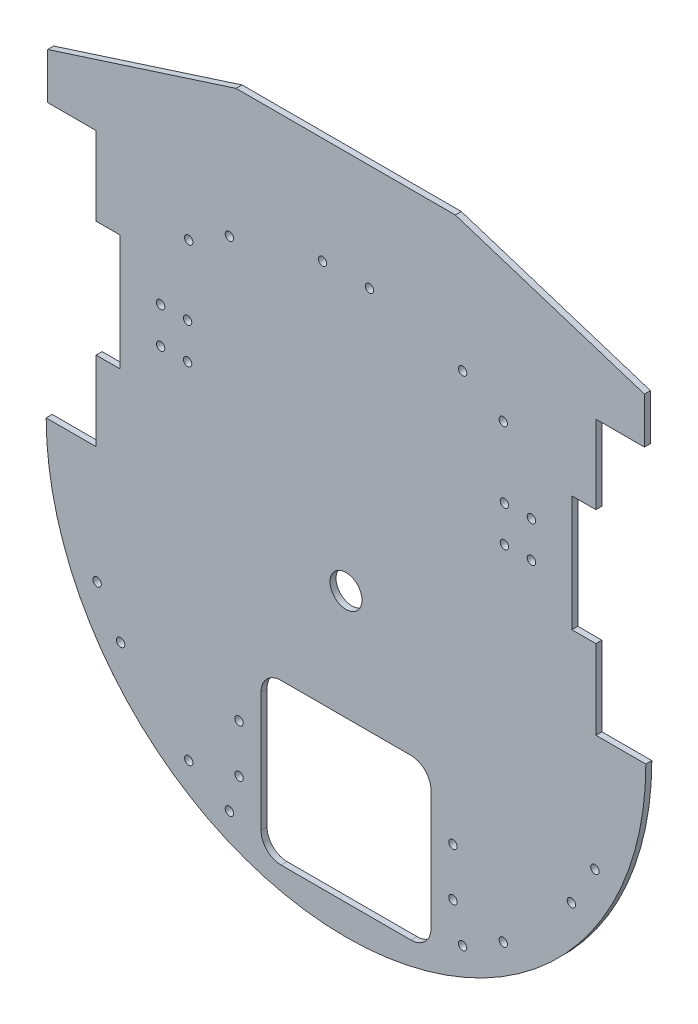
SolidWorks part; units mm, degrees
ref_plane "前视基准面" through (0, 0, 0) normal (0, 0, 1) x (1, 0, 0)
ref_plane "上视基准面" through (0, 0, 0) normal (0, 1, 0) x (1, 0, 0)
ref_plane "右视基准面" through (0, 0, 0) normal (1, 0, 0) x (0, 0, -1)
sketch "草图1" plane through (0, 0, 0) normal (0, 0, 1) x (1, 0, 0)
  line L0 (-172.2675, 0) -> (180.3743, 0) construction
  line L1 (-150, 0) -> (-125.0004, 0)
  line L2 (150, 0) -> (125.0004, 0)
  line L3 (-125.0004, 0) -> (-125.0004, 39.6998)
  line L4 (125.0004, 0) -> (125.0004, 39.6998)
  line L5 (-149.2919, 159.9629) -> (-55, 190.2481)
  line L6 (42.5, -95) -> (42.5, -65)
  line L7 (160.7954, 68.7) -> (-155.1254, 68.7) construction
  line L8 (-42.5, -95) -> (-42.5, -65)
  line L9 (54.6877, 190.2481) -> (149.2919, 159.9629)
  line L10 (42.5, -95) -> (-42.5, -95) construction
  line L11 (-86.0004, 86.026) -> (-86.0004, 54.054) construction
  line L12 (42.5, -95) -> (42.5, -125)
  line L13 (-32.5, -135) -> (32.5, -135)
  line L14 (0, -145) -> (104.3732, -145) construction
  line L15 (-42.5, -125) -> (-42.5, -95)
  line L17 (125.0004, 97.6998) -> (113.0004, 97.6998)
  line L18 (-125.0004, 97.6998) -> (-125.0004, 136.9629)
  line L20 (125.0004, 39.6998) -> (113.0004, 39.6998)
  line L22 (-125.0004, 39.6998) -> (-113.0004, 39.6998)
  line L23 (-125.0004, 97.6998) -> (-113.0004, 97.6998)
  line L24 (125.0004, 136.9629) -> (125.0004, 97.6998)
  line L25 (32.5, -55) -> (-32.5, -55)
  line L27 (0, 25.0818) -> (0, -21.9182) construction
  line L31 (149.2919, -14.5582) -> (149.2919, 172.9128) construction
  line L36 (0, -55) -> (0, -174.5161) construction
  line L46 (-149.2919, 136.9629) -> (-149.2919, 159.9629)
  line L48 (-125.0004, 136.9629) -> (-149.2919, 136.9629)
  line L87 (-149.2919, -14.5582) -> (-149.2919, 172.9128) construction
  line L92 (54.6877, 190.2481) -> (-55, 190.2481)
  line L104 (149.2919, 136.9629) -> (149.2919, 159.9629)
  line L122 (125.0004, 136.9629) -> (149.2919, 136.9629)
  line L125 (-113.0004, 97.6998) -> (-113.0004, 39.6998)
  line L126 (113.0004, 97.6998) -> (113.0004, 39.6998)
  circle A0 centre (-92.7504, 77.7) radius 2.1
  circle A1 centre (-92.7504, 59.7) radius 2.1
  circle A2 centre (-53.5, -83) radius 2.1
  circle A3 centre (-53.5, -107) radius 2.1
  circle A4 centre (53.5, -107) radius 2.1
  circle A5 centre (53.5, -83) radius 2.1
  circle A6 centre (-79.2504, 59.7) radius 2.1
  circle A7 centre (-79.2504, 77.7) radius 2.1
  circle A8 centre (79.2504, 59.7) radius 2.1
  circle A9 centre (92.7504, 59.7) radius 2.1
  arc A10 (-32.5, -135) -> (-42.5, -125) centre (-32.5, -125) cw
  circle A11 centre (79.2504, 77.7) radius 2.1
  circle A12 centre (92.7504, 77.7) radius 2.1
  circle A13 centre (0, 0) radius 8
  circle A15 centre (-58.3242, -124.5205) radius 2.1
  circle A16 centre (-78.6758, -112.7705) radius 2.1
  circle A17 centre (-112.7705, -78.6758) radius 2.1
  circle A18 centre (-124.5205, -58.3242) radius 2.1
  circle A23 centre (-78.6758, 112.7705) radius 2.1
  circle A24 centre (-58.3242, 124.5205) radius 2.1
  circle A25 centre (-11.75, 137) radius 2.1
  circle A26 centre (11.75, 137) radius 2.1
  circle A27 centre (58.3242, 124.5205) radius 2.1
  circle A28 centre (78.6758, 112.7705) radius 2.1
  arc A31 (32.5, -135) -> (42.5, -125) centre (32.5, -125) ccw
  arc A32 (42.5, -65) -> (32.5, -55) centre (32.5, -65) ccw
  circle A35 centre (124.5205, -58.3242) radius 2.1
  circle A36 centre (112.7705, -78.6758) radius 2.1
  circle A37 centre (78.6758, -112.7705) radius 2.1
  circle A38 centre (58.3242, -124.5205) radius 2.1
  arc A41 (-150, 0) -> (150, 0) centre (0, 0) ccw
  arc A43 (-42.5, -65) -> (-32.5, -55) centre (-32.5, -65) cw
  point P105 (0, 0)
  dimension "D5" = 40
  dimension "D6" = 136.9629
  dimension "D7" = 12
  dimension "D8" = 68.7
  dimension "D9" = 11
  dimension "D10" = 6.75
  dimension "D11" = 9
  dimension "D12" = 145
  dimension "D16" = 4.2
  dimension "D18" = 55
  dimension "D19" = 29.0002
  dimension "D21" = 28.9998
  dimension "D41" = 10
  dimension "D47" = 39.263
  dimension "D33" = 39.263
  dimension "D82" = 150
  dimension "D15" = 16
extrude "拉伸1" add sketch "草图1" along normal blind 3
